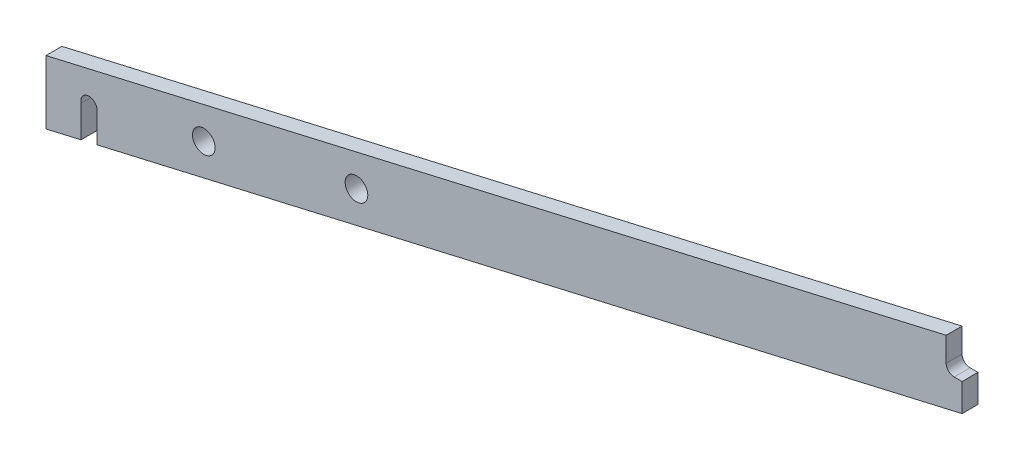
SolidWorks part; units mm, degrees
material "G10"
ref_plane "Front Plane" through (0, 0, 0) normal (0, 0, 1) x (1, 0, 0)
ref_plane "Top Plane" through (0, 0, 0) normal (0, 1, 0) x (1, 0, 0)
ref_plane "Right Plane" through (0, 0, 0) normal (1, 0, 0) x (0, 0, -1)
sketch "Sketch1" plane through (0, 0, 0) normal (0, 0, 1) x (1, 0, 0)
  line L0 (0, 0) -> (91.44, 0) construction
  line L1 (91.44, 0) -> (91.44, 21.1106) construction
  line L2 (91.44, 21.1106) -> (0, 0) construction
  line L3 (91.44, 21.1106) -> (91.44, 27.4606)
  line L4 (91.44, 27.4606) -> (0, 6.35)
  line L5 (0, 6.35) -> (0, 0)
  line L6 (0, 0) -> (91.44, 21.1106)
extrude "Boss-Extrude1" add sketch "Sketch1" along normal blind 1.5875
sketch "Sketch2" plane through (0, 0, 1.5875) normal (0, 0, 1) x (1, 0, 0)
  line L0 (91.44, 27.4606) -> (89.8525, 27.0941)
  line L1 (91.44, 27.4606) -> (0, 6.35) construction
  line L2 (89.8525, 27.0941) -> (89.8525, 24.6825)
  line L3 (90.6462, 23.8887) -> (91.44, 23.8887)
  line L4 (91.44, 21.1106) -> (91.44, 27.4606) construction
  line L5 (5.08, 1.1728) -> (5.08, 4.3478)
  line L6 (0, 0) -> (91.44, 21.1106) construction
  line L8 (3.4925, 3.9813) -> (3.4925, 0.8063)
  line L9 (3.4925, 0.8063) -> (5.08, 1.1728)
  line L10 (5.08, 4.3478) -> (91.44, 24.2856) construction
  line L11 (0, 3.175) -> (3.4925, 3.9813) construction
  line L12 (0, 6.35) -> (0, 0) construction
  arc A0 (5.08, 4.3478) -> (3.4925, 3.9813) centre (4.2863, 4.1646) ccw
  arc A1 (89.8525, 24.6825) -> (90.6462, 23.8887) centre (90.6462, 24.6825) ccw
  circle A2 centre (15.748, 6.8107) radius 1.1303
  circle A3 centre (30.988, 10.3291) radius 1.1303
extrude "Cut-Extrude1" cut sketch "Sketch2" against normal up to next
